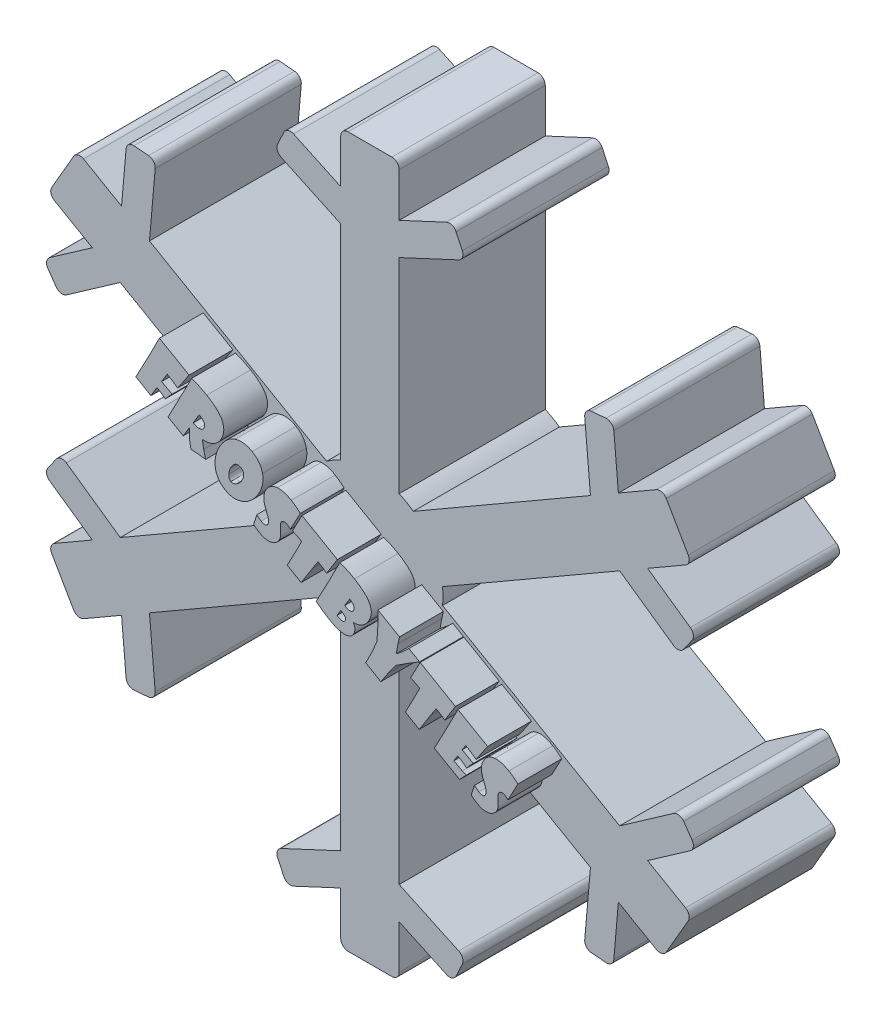
SolidWorks part; units mm, degrees
ref_plane "Front" through (0, 0, 0) normal (0, 0, 1) x (1, 0, 0)
ref_plane "Top" through (0, 0, 0) normal (0, 1, 0) x (1, 0, 0)
ref_plane "Right" through (0, 0, 0) normal (1, 0, 0) x (0, 0, -1)
sketch "Sketch2" plane through (0, 0, 0) normal (0, 0, 1) x (1, 0, 0)
  circle A1 centre (0, 0) radius 5
  dimension "D2" = 10
extrude "Boss-Extrude1" add sketch "Sketch2" against normal blind 10
sketch "Sketch3" plane through (0, 0, 0) normal (0, 0, 1) x (1, 0, 0)
  line L0 (-2, 4.5826) -> (0, 4.5826)
  line L2 (-2, 4.5826) -> (-2, 18.5826)
  line L3 (-2, 18.5826) -> (2, 18.5826)
  line L4 (2, 4.5826) -> (2, 18.5826)
  line L5 (0, 4.5826) -> (2, 4.5826)
  line L6 (0, 4.5826) -> (0, 0) construction
  line L7 (2, 18.5826) -> (6.0784, 20.4844)
  line L8 (6.3202, 21.1488) -> (5.8976, 22.0551)
  line L9 (5.2331, 22.297) -> (2, 20.7893)
  line L10 (2, 20.7893) -> (2, 23.7893)
  line L11 (1.5, 24.2893) -> (-1.5, 24.2893)
  line L12 (0, 4.5826) -> (0, 40.0729) construction
  line L13 (0, 24.2893) -> (0, 18.5826)
  line L14 (-2, 18.5826) -> (-6.0784, 20.4844)
  line L15 (-6.3202, 21.1488) -> (-5.8976, 22.0551)
  line L16 (-5.2331, 22.297) -> (-2, 20.7893)
  line L17 (-2, 20.7893) -> (-2, 23.7893)
  circle A0 centre (0, 0) radius 5 construction
  circle A2 centre (0, 0) radius 23 construction
  arc A3 (-6.0784, 20.4844) -> (-6.3202, 21.1488) centre (-5.8671, 20.9375) cw
  arc A4 (-5.8976, 22.0551) -> (-5.2331, 22.297) centre (-5.4445, 21.8438) cw
  arc A5 (-2, 23.7893) -> (-1.5, 24.2893) centre (-1.5, 23.7893) cw
  arc A6 (1.5, 24.2893) -> (2, 23.7893) centre (1.5, 23.7893) cw
  arc A7 (5.2331, 22.297) -> (5.8976, 22.0551) centre (5.4445, 21.8438) cw
  arc A8 (6.3202, 21.1488) -> (6.0784, 20.4844) centre (5.8671, 20.9375) cw
  point P23 (-6.5315, 20.6957)
  point P26 (-5.6863, 22.5083)
  point P29 (-2, 24.2893)
  point P32 (2, 24.2893)
  point P35 (5.6863, 22.5083)
  point P38 (6.5315, 20.6957)
  circle M17 centre (0, 0) radius 5
  dimension "D3" = 90
  dimension "D4" = 90
  dimension "D9" = 46
  dimension "D11" = 0.5
  dimension "D1" = 4
  dimension "D2" = 14
  dimension "D5" = 25
  dimension "D6" = 2
  dimension "D7" = 3.5
  dimension "D8" = 2
  dimension "D10" = 5
extrude "Boss-Extrude2" add sketch "Sketch3" against normal blind 10 contours L4 L3 L2 M17 | L11 L13 L3 L7 L8 L9 L10 | L17 L16 L15 L14 L3 L13 L11
pattern_circular "CirPattern1" count 6 over 360 about axis through (0, 0, 0) along (0, 0, 1) of "Boss-Extrude2"
sketch "Sketch4" plane through (0, 0, 0) normal (0, 0, 1) x (1, 0, 0)
  line L0 (-16.968, 7.7757) -> (15.218, -10.8068) construction
  line L1 (-4.9686, 0.5592) -> (-17.093, 7.5592) construction
  line L2 (-17.093, 7.5592) -> (-16.968, 7.7757) construction
  line L3 (15.093, -11.0233) -> (15.218, -10.8068) construction
  line L4 (2.9686, -4.0233) -> (15.093, -11.0233) construction
  text T0 "Frostbytes" font "Showcard Gothic" height 3.5
  dimension "D1" = 90
  dimension "D2" = 90
  dimension "D3" = 0.25
extrude "Boss-Extrude3" add sketch "Sketch4" along normal blind 3
